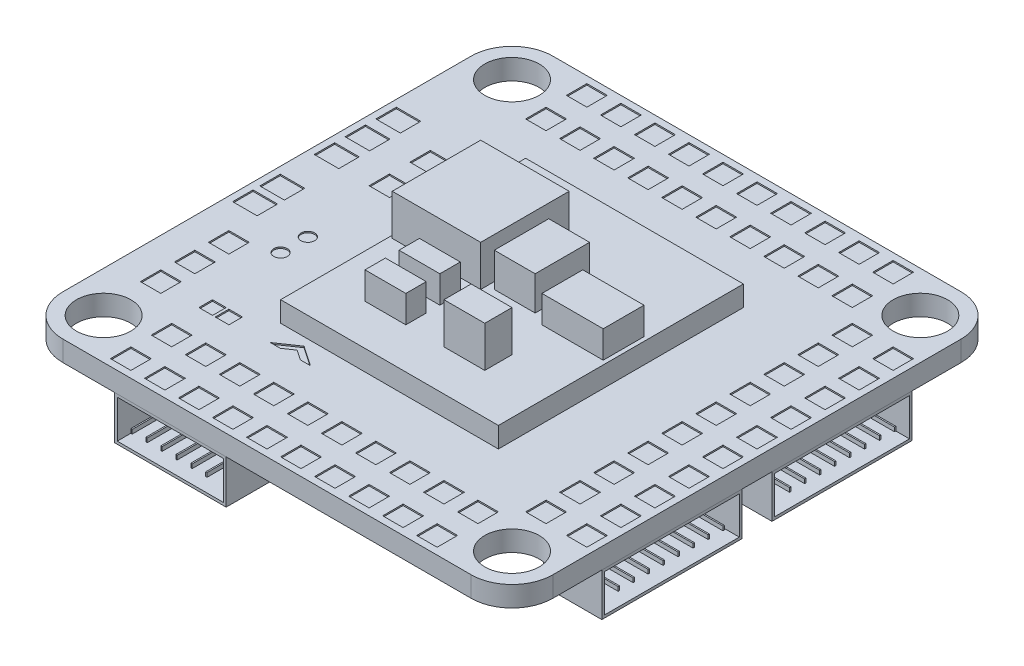
SolidWorks part; units mm, degrees
ref_plane "Front Plane" through (0, 0, 0) normal (0, 0, 1) x (1, 0, 0)
ref_plane "Top Plane" through (0, 0, 0) normal (0, 1, 0) x (1, 0, 0)
ref_plane "Right Plane" through (0, 0, 0) normal (1, 0, 0) x (0, 0, -1)
sketch "Sketch1" plane through (0, 0, 0) normal (0, 1, 0) x (1, 0, 0)
  line L1 (-15, 18) -> (15, 18)
  line L2 (-18, 15) -> (-18, -15)
  line L3 (-15, -18) -> (15, -18)
  line L4 (18, 15) -> (18, -15)
  line L5 (-18, 18) -> (18, -18) construction
  line L6 (-18, -18) -> (18, 18) construction
  circle A0 centre (-15, 15) radius 2
  circle A1 centre (15, 15) radius 2
  circle A2 centre (15, -15) radius 2
  circle A3 centre (-15, -15) radius 2
  arc A4 (-18, -15) -> (-15, -18) centre (-15, -15) ccw
  arc A5 (15, -18) -> (18, -15) centre (15, -15) ccw
  arc A6 (15, 18) -> (18, 15) centre (15, 15) cw
  arc A7 (-18, 15) -> (-15, 18) centre (-15, 15) cw
  point P0 (0, 0)
  dimension "D3" = 4
  dimension "D4" = 3
  dimension "D5" = 3
  dimension "D8" = 30
  dimension "D9" = 30
  dimension "D10" = 3
  dimension "D1" = 36
  dimension "D2" = 36
  dimension "D6" = 2
  dimension "D7" = 2
extrude "Boss-Extrude1" add sketch "Sketch1" along normal blind 1.5
sketch "Sketch2" plane through (0, 1.5, 0) normal (0, 1, 0) x (1, 0, 0)
  line L1 (-8, 9) -> (8, 9)
  line L2 (-8, 9) -> (-8, -9)
  line L3 (-8, -9) -> (8, -9)
  line L4 (8, 9) -> (8, -9)
  line L5 (-8, 9) -> (8, -9) construction
  line L6 (-8, -9) -> (8, 9) construction
  point P0 (0, 0)
  dimension "D1" = 16
  dimension "D2" = 18
extrude "Boss-Extrude2" add sketch "Sketch2" along normal blind 1.5
sketch "Sketch3" plane through (0, 3, 0) normal (0, 1, 0) x (1, 0, 0)
  line L0 (8, 9) -> (-8, 9) construction
  line L1 (-7.8, 5.5) -> (-1.3, 5.5)
  line L2 (-7.8, 5.5) -> (-7.8, -1)
  line L3 (-7.8, -1) -> (-1.3, -1)
  line L4 (-1.3, 5.5) -> (-1.3, -1)
  line L5 (-7.8, 5.5) -> (-1.3, -1) construction
  line L6 (-7.8, -1) -> (-1.3, 5.5) construction
  line L7 (8, -9) -> (8, 9) construction
  point P0 (-4.55, 2.25)
  dimension "D1" = 6.5
  dimension "D2" = 6.5
  dimension "D3" = 3.5
  dimension "D4" = 9.3
extrude "Boss-Extrude3" add sketch "Sketch3" along normal blind 3
sketch "Sketch4" plane through (0, 3, 0) normal (0, 1, 0) x (1, 0, 0)
  line L0 (-7.8, -1) -> (-1.3, -1) construction
  line L1 (-4.8, -2) -> (-1.8, -2)
  line L2 (-4.8, -2) -> (-4.8, -3.5)
  line L3 (-4.8, -3.5) -> (-1.8, -3.5)
  line L4 (-1.8, -2) -> (-1.8, -3.5)
  line L5 (-4.8, -2) -> (-1.8, -3.5) construction
  line L6 (-4.8, -3.5) -> (-1.8, -2) construction
  line L7 (-1.3, -1) -> (-1.3, 5.5) construction
  line L8 (-4.8, -4.5) -> (-4.8, -6)
  line L9 (-4.8, -4.5) -> (-1.8, -4.5)
  line L10 (-1.8, -4.5) -> (-1.8, -6)
  line L11 (-4.8, -6) -> (-1.8, -6)
  point P0 (-3.3, -2.75)
  dimension "D1" = 1.5
  dimension "D2" = 3
  dimension "D3" = 1
  dimension "D4" = 0.5
  dimension "D5" = 2
extrude "Boss-Extrude4" add sketch "Sketch4" along normal blind 2
sketch "Sketch5" plane through (0, 3, 0) normal (0, 1, 0) x (1, 0, 0)
  line L0 (8, -9) -> (8, 9) construction
  line L1 (1, -4) -> (4, -4)
  line L2 (1, -4) -> (1, -6)
  line L3 (1, -6) -> (4, -6)
  line L4 (4, -4) -> (4, -6)
  line L5 (1, -4) -> (4, -6) construction
  line L6 (1, -6) -> (4, -4) construction
  line L7 (-8, -9) -> (8, -9) construction
  point P0 (2.5, -5)
  dimension "D1" = 2
  dimension "D2" = 3
  dimension "D3" = 4
  dimension "D4" = 3
extrude "Boss-Extrude5" add sketch "Sketch5" along normal blind 3
sketch "Sketch6" plane through (0, 3, 0) normal (0, 1, 0) x (1, 0, 0)
  line L0 (-1.3, -1) -> (-1.3, 5.5) construction
  line L1 (-0.8, 3.5) -> (2.2, 3.5)
  line L2 (-0.8, 3.5) -> (-0.8, -0.5)
  line L3 (-0.8, -0.5) -> (2.2, -0.5)
  line L4 (2.2, 3.5) -> (2.2, -0.5)
  line L5 (-0.8, 3.5) -> (2.2, -0.5) construction
  line L6 (-0.8, -0.5) -> (2.2, 3.5) construction
  line L8 (-7.8, -1) -> (-1.3, -1) construction
  point P0 (0.7, 1.5)
  dimension "D1" = 4
  dimension "D2" = 3
  dimension "D3" = 0.5
  dimension "D4" = 0.5
extrude "Boss-Extrude6" add sketch "Sketch6" along normal blind 2.5
sketch "Sketch7" plane through (0, 3, 0) normal (0, 1, 0) x (1, 0, 0)
  line L0 (8, -9) -> (8, 9) construction
  line L1 (3.2, 2) -> (7.7, 2)
  line L2 (3.2, 2) -> (3.2, -1)
  line L3 (3.2, -1) -> (7.7, -1)
  line L4 (7.7, 2) -> (7.7, -1)
  line L5 (3.2, 2) -> (7.7, -1) construction
  line L6 (3.2, -1) -> (7.7, 2) construction
  line L7 (8, 9) -> (-8, 9) construction
  point P0 (5.45, 0.5)
  dimension "D1" = 4.5
  dimension "D2" = 3
  dimension "D3" = 0.3
  dimension "D4" = 7
extrude "Boss-Extrude7" add sketch "Sketch7" along normal blind 2
sketch "Sketch8" plane through (0, 1.5, 0) normal (0, 1, 0) x (1, 0, 0)
  line L0 (-5.6809, -9.5944) -> (-7.1537, -10.6043)
  line L1 (-7.1537, -10.6043) -> (-6.4173, -10.6043)
  line L2 (-6.4173, -10.6043) -> (-5.6809, -10.0993)
  line L3 (-5.6809, -9.5944) -> (-5.6809, -10.6043) construction
  line L4 (-4.9445, -10.6043) -> (-5.6809, -10.0993)
  line L5 (-4.2081, -10.6043) -> (-4.9445, -10.6043)
  line L6 (-5.6809, -9.5944) -> (-4.2081, -10.6043)
extrude "Cut-Extrude1" cut sketch "Sketch8" against normal blind 0.1
sketch "Sketch9" plane through (0, 1.5, 0) normal (0, 1, 0) x (1, 0, 0)
  line L0 (-18, 15) -> (-18, -15) construction
  line L1 (-12, -13) -> (-10.5, -13)
  line L2 (-12, -13) -> (-12, -14.5)
  line L3 (-12, -14.5) -> (-10.5, -14.5)
  line L4 (-10.5, -13) -> (-10.5, -14.5)
  line L5 (-12, -13) -> (-10.5, -14.5) construction
  line L6 (-12, -14.5) -> (-10.5, -13) construction
  line L7 (-15, -18) -> (15, -18) construction
  line L8 (-9.5, -13) -> (-9.5, -14.5)
  line L9 (-9.5, -13) -> (-8, -13)
  line L10 (-8, -13) -> (-8, -14.5)
  line L11 (-9.5, -14.5) -> (-8, -14.5)
  line L12 (-7, -13) -> (-7, -14.5)
  line L13 (-7, -13) -> (-5.5, -13)
  line L14 (-5.5, -13) -> (-5.5, -14.5)
  line L15 (-7, -14.5) -> (-5.5, -14.5)
  line L16 (-4.5, -13) -> (-4.5, -14.5)
  line L17 (-4.5, -13) -> (-3, -13)
  line L18 (-3, -13) -> (-3, -14.5)
  line L19 (-4.5, -14.5) -> (-3, -14.5)
  line L20 (-2, -13) -> (-2, -14.5)
  line L21 (-2, -13) -> (-0.5, -13)
  line L22 (-0.5, -13) -> (-0.5, -14.5)
  line L23 (-2, -14.5) -> (-0.5, -14.5)
  line L24 (0.5, -13) -> (0.5, -14.5)
  line L25 (0.5, -13) -> (2, -13)
  line L26 (2, -13) -> (2, -14.5)
  line L27 (0.5, -14.5) -> (2, -14.5)
  line L28 (3, -13) -> (3, -14.5)
  line L29 (3, -13) -> (4.5, -13)
  line L30 (4.5, -13) -> (4.5, -14.5)
  line L31 (3, -14.5) -> (4.5, -14.5)
  line L32 (5.5, -13) -> (5.5, -14.5)
  line L33 (5.5, -13) -> (7, -13)
  line L34 (7, -13) -> (7, -14.5)
  line L35 (5.5, -14.5) -> (7, -14.5)
  line L36 (8, -13) -> (8, -14.5)
  line L37 (8, -13) -> (9.5, -13)
  line L38 (9.5, -13) -> (9.5, -14.5)
  line L39 (8, -14.5) -> (9.5, -14.5)
  line L40 (10.5, -13) -> (10.5, -14.5)
  line L41 (10.5, -13) -> (12, -13)
  line L42 (12, -13) -> (12, -14.5)
  line L43 (10.5, -14.5) -> (12, -14.5)
  line L44 (-9.5, -16) -> (-9.5, -17.5)
  line L45 (-9.5, -16) -> (-8, -16)
  line L46 (-8, -16) -> (-8, -17.5)
  line L47 (-9.5, -17.5) -> (-8, -17.5)
  line L48 (-7, -16) -> (-7, -17.5)
  line L49 (-7, -16) -> (-5.5, -16)
  line L50 (-5.5, -16) -> (-5.5, -17.5)
  line L51 (-7, -17.5) -> (-5.5, -17.5)
  line L52 (-4.5, -16) -> (-4.5, -17.5)
  line L53 (-4.5, -16) -> (-3, -16)
  line L54 (-3, -16) -> (-3, -17.5)
  line L55 (-4.5, -17.5) -> (-3, -17.5)
  line L56 (-2, -16) -> (-2, -17.5)
  line L57 (-2, -16) -> (-0.5, -16)
  line L58 (-0.5, -16) -> (-0.5, -17.5)
  line L59 (-2, -17.5) -> (-0.5, -17.5)
  line L60 (0.5, -16) -> (0.5, -17.5)
  line L61 (0.5, -16) -> (2, -16)
  line L62 (2, -16) -> (2, -17.5)
  line L63 (0.5, -17.5) -> (2, -17.5)
  line L64 (3, -16) -> (3, -17.5)
  line L65 (3, -16) -> (4.5, -16)
  line L66 (4.5, -16) -> (4.5, -17.5)
  line L67 (3, -17.5) -> (4.5, -17.5)
  line L68 (5.5, -16) -> (5.5, -17.5)
  line L69 (5.5, -16) -> (7, -16)
  line L70 (7, -16) -> (7, -17.5)
  line L71 (5.5, -17.5) -> (7, -17.5)
  line L72 (8, -16) -> (8, -17.5)
  line L73 (8, -16) -> (9.5, -16)
  line L74 (9.5, -16) -> (9.5, -17.5)
  line L75 (8, -17.5) -> (9.5, -17.5)
  line L76 (10.5, -16) -> (10.5, -17.5)
  line L77 (10.5, -16) -> (12, -16)
  line L78 (12, -16) -> (12, -17.5)
  line L79 (10.5, -17.5) -> (12, -17.5)
  line L80 (-12, -16) -> (-12, -17.5)
  line L81 (-12, -16) -> (-10.5, -16)
  line L82 (-10.5, -16) -> (-10.5, -17.5)
  line L83 (-12, -17.5) -> (-10.5, -17.5)
  line L84 (-18, 0) -> (18, 0) construction
  line L85 (18, -15) -> (18, 15) construction
  line L86 (-15, 15) -> (15, -15) construction
  line L87 (14.5, 12) -> (13, 10.5) construction
  line L88 (13, 12) -> (14.5, 10.5) construction
  line L89 (17.5, 12) -> (17.5, 10.5)
  line L90 (16, 10.5) -> (17.5, 10.5)
  line L91 (16, 12) -> (16, 10.5)
  line L92 (16, 12) -> (17.5, 12)
  line L93 (17.5, -10.5) -> (17.5, -12)
  line L94 (16, -12) -> (17.5, -12)
  line L95 (16, -10.5) -> (16, -12)
  line L96 (16, -10.5) -> (17.5, -10.5)
  line L97 (17.5, -8) -> (17.5, -9.5)
  line L98 (16, -9.5) -> (17.5, -9.5)
  line L99 (16, -8) -> (16, -9.5)
  line L100 (16, -8) -> (17.5, -8)
  line L101 (17.5, -5.5) -> (17.5, -7)
  line L102 (16, -7) -> (17.5, -7)
  line L103 (16, -5.5) -> (16, -7)
  line L104 (16, -5.5) -> (17.5, -5.5)
  line L105 (17.5, -3) -> (17.5, -4.5)
  line L106 (16, -4.5) -> (17.5, -4.5)
  line L107 (16, -3) -> (16, -4.5)
  line L108 (16, -3) -> (17.5, -3)
  line L109 (17.5, -0.5) -> (17.5, -2)
  line L110 (16, -2) -> (17.5, -2)
  line L111 (16, -0.5) -> (16, -2)
  line L112 (16, -0.5) -> (17.5, -0.5)
  line L113 (17.5, 2) -> (17.5, 0.5)
  line L114 (16, 0.5) -> (17.5, 0.5)
  line L115 (16, 2) -> (16, 0.5)
  line L116 (16, 2) -> (17.5, 2)
  line L117 (17.5, 4.5) -> (17.5, 3)
  line L118 (16, 3) -> (17.5, 3)
  line L119 (16, 4.5) -> (16, 3)
  line L120 (16, 4.5) -> (17.5, 4.5)
  line L121 (17.5, 7) -> (17.5, 5.5)
  line L122 (16, 5.5) -> (17.5, 5.5)
  line L123 (16, 7) -> (16, 5.5)
  line L124 (16, 7) -> (17.5, 7)
  line L125 (17.5, 9.5) -> (17.5, 8)
  line L126 (16, 8) -> (17.5, 8)
  line L127 (16, 9.5) -> (16, 8)
  line L128 (16, 9.5) -> (17.5, 9.5)
  line L129 (14.5, -10.5) -> (14.5, -12)
  line L130 (13, -12) -> (14.5, -12)
  line L131 (13, -10.5) -> (13, -12)
  line L132 (13, -10.5) -> (14.5, -10.5)
  line L133 (14.5, -8) -> (14.5, -9.5)
  line L134 (13, -9.5) -> (14.5, -9.5)
  line L135 (13, -8) -> (13, -9.5)
  line L136 (13, -8) -> (14.5, -8)
  line L137 (14.5, -5.5) -> (14.5, -7)
  line L138 (13, -7) -> (14.5, -7)
  line L139 (13, -5.5) -> (13, -7)
  line L140 (13, -5.5) -> (14.5, -5.5)
  line L141 (14.5, -3) -> (14.5, -4.5)
  line L142 (13, -4.5) -> (14.5, -4.5)
  line L143 (13, -3) -> (13, -4.5)
  line L144 (13, -3) -> (14.5, -3)
  line L145 (14.5, -0.5) -> (14.5, -2)
  line L146 (13, -2) -> (14.5, -2)
  line L147 (13, -0.5) -> (13, -2)
  line L148 (13, -0.5) -> (14.5, -0.5)
  line L149 (14.5, 2) -> (14.5, 0.5)
  line L150 (13, 0.5) -> (14.5, 0.5)
  line L151 (13, 2) -> (13, 0.5)
  line L152 (13, 2) -> (14.5, 2)
  line L153 (14.5, 4.5) -> (14.5, 3)
  line L154 (13, 3) -> (14.5, 3)
  line L155 (13, 4.5) -> (13, 3)
  line L156 (13, 4.5) -> (14.5, 4.5)
  line L157 (14.5, 7) -> (14.5, 5.5)
  line L158 (13, 5.5) -> (14.5, 5.5)
  line L159 (13, 7) -> (13, 5.5)
  line L160 (13, 7) -> (14.5, 7)
  line L161 (14.5, 9.5) -> (14.5, 8)
  line L162 (13, 8) -> (14.5, 8)
  line L163 (13, 9.5) -> (13, 8)
  line L164 (13, 9.5) -> (14.5, 9.5)
  line L165 (13, 10.5) -> (14.5, 10.5)
  line L166 (14.5, 12) -> (14.5, 10.5)
  line L167 (13, 12) -> (14.5, 12)
  line L168 (13, 12) -> (13, 10.5)
  line L169 (-12, 14.5) -> (-10.5, 13) construction
  line L170 (-12, 13) -> (-10.5, 14.5) construction
  line L171 (-12, 17.5) -> (-10.5, 17.5)
  line L172 (-10.5, 16) -> (-10.5, 17.5)
  line L173 (-12, 16) -> (-10.5, 16)
  line L174 (-12, 16) -> (-12, 17.5)
  line L175 (10.5, 17.5) -> (12, 17.5)
  line L176 (12, 16) -> (12, 17.5)
  line L177 (10.5, 16) -> (12, 16)
  line L178 (10.5, 16) -> (10.5, 17.5)
  line L179 (8, 17.5) -> (9.5, 17.5)
  line L180 (9.5, 16) -> (9.5, 17.5)
  line L181 (8, 16) -> (9.5, 16)
  line L182 (8, 16) -> (8, 17.5)
  line L183 (5.5, 17.5) -> (7, 17.5)
  line L184 (7, 16) -> (7, 17.5)
  line L185 (5.5, 16) -> (7, 16)
  line L186 (5.5, 16) -> (5.5, 17.5)
  line L187 (3, 17.5) -> (4.5, 17.5)
  line L188 (4.5, 16) -> (4.5, 17.5)
  line L189 (3, 16) -> (4.5, 16)
  line L190 (3, 16) -> (3, 17.5)
  line L191 (0.5, 17.5) -> (2, 17.5)
  line L192 (2, 16) -> (2, 17.5)
  line L193 (0.5, 16) -> (2, 16)
  line L194 (0.5, 16) -> (0.5, 17.5)
  line L195 (-2, 17.5) -> (-0.5, 17.5)
  line L196 (-0.5, 16) -> (-0.5, 17.5)
  line L197 (-2, 16) -> (-0.5, 16)
  line L198 (-2, 16) -> (-2, 17.5)
  line L199 (-4.5, 17.5) -> (-3, 17.5)
  line L200 (-3, 16) -> (-3, 17.5)
  line L201 (-4.5, 16) -> (-3, 16)
  line L202 (-4.5, 16) -> (-4.5, 17.5)
  line L203 (-7, 17.5) -> (-5.5, 17.5)
  line L204 (-5.5, 16) -> (-5.5, 17.5)
  line L205 (-7, 16) -> (-5.5, 16)
  line L206 (-7, 16) -> (-7, 17.5)
  line L207 (-9.5, 17.5) -> (-8, 17.5)
  line L208 (-8, 16) -> (-8, 17.5)
  line L209 (-9.5, 16) -> (-8, 16)
  line L210 (-9.5, 16) -> (-9.5, 17.5)
  line L211 (10.5, 14.5) -> (12, 14.5)
  line L212 (12, 13) -> (12, 14.5)
  line L213 (10.5, 13) -> (12, 13)
  line L214 (10.5, 13) -> (10.5, 14.5)
  line L215 (8, 14.5) -> (9.5, 14.5)
  line L216 (9.5, 13) -> (9.5, 14.5)
  line L217 (8, 13) -> (9.5, 13)
  line L218 (8, 13) -> (8, 14.5)
  line L219 (5.5, 14.5) -> (7, 14.5)
  line L220 (7, 13) -> (7, 14.5)
  line L221 (5.5, 13) -> (7, 13)
  line L222 (5.5, 13) -> (5.5, 14.5)
  line L223 (3, 14.5) -> (4.5, 14.5)
  line L224 (4.5, 13) -> (4.5, 14.5)
  line L225 (3, 13) -> (4.5, 13)
  line L226 (3, 13) -> (3, 14.5)
  line L227 (0.5, 14.5) -> (2, 14.5)
  line L228 (2, 13) -> (2, 14.5)
  line L229 (0.5, 13) -> (2, 13)
  line L230 (0.5, 13) -> (0.5, 14.5)
  line L231 (-2, 14.5) -> (-0.5, 14.5)
  line L232 (-0.5, 13) -> (-0.5, 14.5)
  line L233 (-2, 13) -> (-0.5, 13)
  line L234 (-2, 13) -> (-2, 14.5)
  line L235 (-4.5, 14.5) -> (-3, 14.5)
  line L236 (-3, 13) -> (-3, 14.5)
  line L237 (-4.5, 13) -> (-3, 13)
  line L238 (-4.5, 13) -> (-4.5, 14.5)
  line L239 (-7, 14.5) -> (-5.5, 14.5)
  line L240 (-5.5, 13) -> (-5.5, 14.5)
  line L241 (-7, 13) -> (-5.5, 13)
  line L242 (-7, 13) -> (-7, 14.5)
  line L243 (-9.5, 14.5) -> (-8, 14.5)
  line L244 (-8, 13) -> (-8, 14.5)
  line L245 (-9.5, 13) -> (-8, 13)
  line L246 (-9.5, 13) -> (-9.5, 14.5)
  line L247 (-10.5, 13) -> (-10.5, 14.5)
  line L248 (-12, 14.5) -> (-10.5, 14.5)
  line L249 (-12, 13) -> (-12, 14.5)
  line L250 (-12, 13) -> (-10.5, 13)
  line L251 (-10.8, -10) -> (-10.8, -11)
  line L252 (-12, -10) -> (-11, -10)
  line L253 (-12, -10) -> (-12, -11)
  line L254 (-12, -11) -> (-11, -11)
  line L255 (-11, -10) -> (-11, -11)
  line L256 (-12, -10) -> (-11, -11) construction
  line L257 (-12, -11) -> (-11, -10) construction
  line L258 (-10.8, -10) -> (-9.8, -10)
  line L259 (-9.8, -10) -> (-9.8, -11)
  line L260 (-10.8, -11) -> (-9.8, -11)
  line L261 (-10.5, -16) -> (-12, -17.5) construction
  line L262 (-8, -13) -> (-9.5, -14.5) construction
  line L263 (-8, -16) -> (-9.5, -17.5) construction
  line L264 (-12, -16) -> (-10.5, -17.5) construction
  line L265 (-9.5, -16) -> (-8, -17.5) construction
  line L266 (-9.5, -13) -> (-8, -14.5) construction
  line L267 (-10.8, -10) -> (-9.8, -11) construction
  line L268 (-9.8, -10) -> (-10.8, -11) construction
  line L269 (-7, -13) -> (-5.5, -14.5) construction
  line L270 (-5.5, -16) -> (-7, -17.5) construction
  line L271 (-4.5, -14.5) -> (-3, -13) construction
  line L272 (15, 18) -> (-15, 18) construction
  line L273 (-15.7, 9) -> (-17.5, 9)
  line L274 (-15.7, 9) -> (-15.7, 7.5)
  line L275 (-15.7, 7.5) -> (-17.5, 7.5)
  line L276 (-17.5, 9) -> (-17.5, 7.5)
  line L277 (-15.7, 9) -> (-17.5, 7.5) construction
  line L278 (-15.7, 7.5) -> (-17.5, 9) construction
  line L279 (-15.7, 6.7373) -> (-15.7, 5.2373)
  line L280 (-15.7, 6.7373) -> (-17.5, 6.7373)
  line L281 (-17.5, 6.7373) -> (-17.5, 5.2373)
  line L282 (-15.7, 5.2373) -> (-17.5, 5.2373)
  line L283 (-15.7, 4.4745) -> (-15.7, 2.9745)
  line L284 (-15.7, 4.4745) -> (-17.5, 4.4745)
  line L285 (-17.5, 4.4745) -> (-17.5, 2.9745)
  line L286 (-15.7, 2.9745) -> (-17.5, 2.9745)
  line L287 (-15.7, -1.5255) -> (-15.7, -3.0255)
  line L288 (-15.7, 0.4745) -> (-17.5, 0.4745)
  line L289 (-15.7, 0.4745) -> (-15.7, -1.0255)
  line L290 (-15.7, -1.0255) -> (-17.5, -1.0255)
  line L291 (-17.5, 0.4745) -> (-17.5, -1.0255)
  line L292 (-15.7, 0.4745) -> (-17.5, -1.0255) construction
  line L293 (-15.7, -1.0255) -> (-17.5, 0.4745) construction
  line L294 (-15.7, -1.5255) -> (-17.5, -1.5255)
  line L295 (-17.5, -1.5255) -> (-17.5, -3.0255)
  line L296 (-15.7, -3.0255) -> (-17.5, -3.0255)
  line L297 (-12, 4.5) -> (-12, 3)
  line L298 (-12, 7.5) -> (-13.5, 7.5)
  line L299 (-12, 7.5) -> (-12, 6)
  line L300 (-12, 6) -> (-13.5, 6)
  line L301 (-13.5, 7.5) -> (-13.5, 6)
  line L302 (-12, 7.5) -> (-13.5, 6) construction
  line L303 (-12, 6) -> (-13.5, 7.5) construction
  line L304 (-12, 4.5) -> (-13.5, 4.5)
  line L305 (-13.5, 4.5) -> (-13.5, 3)
  line L306 (-12, 3) -> (-13.5, 3)
  line L307 (-14.3, -7.5) -> (-14.3, -9)
  line L308 (-14.3, -10) -> (-15.8, -10)
  line L309 (-14.3, -10) -> (-14.3, -11.5)
  line L310 (-14.3, -11.5) -> (-15.8, -11.5)
  line L311 (-15.8, -10) -> (-15.8, -11.5)
  line L312 (-14.3, -10) -> (-15.8, -11.5) construction
  line L313 (-14.3, -11.5) -> (-15.8, -10) construction
  line L314 (-14.3, -7.5) -> (-15.8, -7.5)
  line L315 (-15.8, -7.5) -> (-15.8, -9)
  line L316 (-14.3, -9) -> (-15.8, -9)
  line L317 (-14.3, -5) -> (-14.3, -6.5)
  line L318 (-14.3, -5) -> (-15.8, -5)
  line L319 (-15.8, -5) -> (-15.8, -6.5)
  line L320 (-14.3, -6.5) -> (-15.8, -6.5)
  circle A0 centre (-12.5, -4.5) radius 0.5
  circle A1 centre (-12.5, -2.5) radius 0.5
  point P0 (-11.25, -13.75)
  point P173 (13.75, 11.25)
  point P254 (-11.25, 13.75)
  point P255 (-11.5, -10.5)
  point P260 (-16.6, 8.25)
  point P271 (-16.6, -0.2755)
  point P284 (-12.75, 6.75)
  point P293 (-15.05, -10.75)
  dimension "D32" = 1
  dimension "D33" = 5.5
  dimension "D34" = 13.5
  dimension "D1" = 1.5
  dimension "D2" = 1.5
  dimension "D3" = 6
  dimension "D4" = 3.5
  dimension "D7" = 1
  dimension "D8" = 1
  dimension "D9" = 0
  dimension "D10" = 2
  dimension "D12" = 9
  dimension "D13" = 1.5
  dimension "D14" = 1.8
  dimension "D16" = 1.5
  dimension "D17" = 1.8
  dimension "D18" = 2.5
  dimension "D19" = 0.5
  dimension "D20" = 0.5
  dimension "D22" = 1.5
  dimension "D23" = 1.5
  dimension "D24" = 4.5
  dimension "D25" = 10.5
  dimension "D27" = 1.5
  dimension "D28" = 1.5
  dimension "D29" = 6.5
  dimension "D30" = 2.2
  dimension "D5" = 10
  dimension "D6" = 2
  dimension "D11" = 2
  dimension "D15" = 3
  dimension "D21" = 2
  dimension "D26" = 2
  dimension "D31" = 3
  dimension "D35" = 2
extrude "Cut-Extrude2" cut sketch "Sketch9" against normal blind 0.1
sketch "Sketch12" plane through (-18, 0, 0) normal (-1, 0, 0) x (0, 0, 1)
  line L1 (-8.7, 0) -> (-3.1, 0)
  line L3 (-8.7, -3.2) -> (-3.1, -3.2)
  line L6 (-18, 1.5) -> (-18, 0) construction
  line L7 (-15, 0) -> (15, 0) construction
  arc A0 (-3.1, 0) -> (-3.1, -3.2) centre (-3.1, -1.6) cw
  arc A1 (-8.7, -3.2) -> (-8.7, 0) centre (-8.7, -1.6) cw
  dimension "D1" = 1.6
  dimension "D2" = 1.6
  dimension "D3" = 9.3
  dimension "D6" = 5.6
  dimension "D4" = 5.6
  dimension "D5" = 3.2
  dimension "D7" = 3.2
extrude "Boss-Extrude8" add sketch "Sketch12" along normal blind 1.5 and the other way blind 5.7
sketch "Sketch13" plane through (-19.5, 0, 0) normal (-1, 0, 0) x (0, 0, 1)
  line L0 (-3.1, 0) -> (-8.7, 0) construction
  line L1 (-8.7, 0) -> (-3.1, 0)
  line L2 (-3.1, -3.2) -> (-8.7, -3.2)
  line L3 (-3.1, -3.1) -> (-8.7, -3.1)
  line L4 (-8.7, -0.1) -> (-3.1, -0.1)
  line L5 (-8.7, -1.6) -> (-3.1, -1.6) construction
  line L6 (-8.7, -1.8) -> (-3.1, -1.8)
  line L7 (-8.7, -1.4) -> (-3.1, -1.4)
  arc A0 (-8.7, -3.2) -> (-8.7, 0) centre (-8.7, -1.6) cw
  arc A1 (-3.1, 0) -> (-3.1, -3.2) centre (-3.1, -1.6) cw
  arc A2 (-3.1, -3.2) -> (-3.1, 0) centre (-3.1, -1.6) ccw construction
  arc A3 (-8.7, -3.1) -> (-8.7, -0.1) centre (-8.7, -1.6) cw
  arc A4 (-3.1, -0.1) -> (-3.1, -3.1) centre (-3.1, -1.6) cw
  arc A5 (-3.1, -1.4) -> (-3.1, -1.8) centre (-3.1, -1.6) cw
  arc A6 (-8.7, -1.8) -> (-8.7, -1.4) centre (-8.7, -1.6) cw
  dimension "D1" = 0.1
  dimension "D2" = 0.2
  dimension "D3" = 0.2
extrude "Cut-Extrude3" cut sketch "Sketch13" against normal blind 6 contours A4 L4 A3 L3 L6 A6 L7 A5
sketch "Sketch15" plane through (0, 0, 0) normal (0, -1, 0) x (1, 0, 0)
  line L1 (-17.7, 5) -> (-15.2, 5)
  line L2 (-17.7, 5) -> (-17.7, 9.5)
  line L3 (-17.7, 9.5) -> (-15.2, 9.5)
  line L4 (-15.2, 5) -> (-15.2, 9.5)
  line L5 (-17.7, 5) -> (-15.2, 9.5) construction
  line L6 (-17.7, 9.5) -> (-15.2, 5) construction
  line L8 (-12.3, -1.5) -> (-19.5, -1.5) construction
  line L9 (-18, -3.1) -> (-18, 15) construction
  point P0 (-16.45, 7.25)
  dimension "D1" = 6.5
  dimension "D2" = 2.8
  dimension "D3" = 2.5
  dimension "D4" = 4.5
extrude "Boss-Extrude9" add sketch "Sketch15" along normal blind 2
sketch "Sketch16" plane through (-17.7, 0, 0) normal (-1, 0, 0) x (0, 0, 1)
  line L0 (5, 0) -> (9.5, -2) construction
  line L1 (9.5, 0) -> (5, -2) construction
  line L3 (6.25, -0.5) -> (8.25, -0.5)
  line L4 (6.25, -0.5) -> (6.25, -1.5)
  line L5 (6.25, -1.5) -> (8.25, -1.5)
  line L6 (8.25, -0.5) -> (8.25, -1.5)
  line L7 (6.25, -0.5) -> (8.25, -1.5) construction
  line L8 (6.25, -1.5) -> (8.25, -0.5) construction
  point P8 (7.25, -1)
  dimension "D1" = 2
  dimension "D2" = 1
extrude "Boss-Extrude10" add sketch "Sketch16" along normal blind 1
sketch "Sketch17" plane through (0, 0, 18) normal (0, 0, 1) x (1, 0, 0)
  line L0 (-15, 0) -> (15, 0) construction
  line L1 (-11.2, 0) -> (-3, 0)
  line L2 (-11.2, 0) -> (-11.2, -3.2)
  line L3 (-11.2, -3.2) -> (-3, -3.2)
  line L4 (-3, 0) -> (-3, -3.2)
  line L5 (-18, 1.5) -> (-18, 0) construction
  dimension "D1" = 15
  dimension "D2" = 8.2
  dimension "D3" = 3.2
extrude "Boss-Extrude11" add sketch "Sketch17" against normal blind 4.5 separate body
sketch "Sketch18" plane through (0, 0, 18) normal (0, 0, 1) x (1, 0, 0)
  line L0 (-11.2, 0) -> (-11.2, -3.2)
  line L1 (-11.2, -3.2) -> (-3, -3.2)
  line L2 (-3, -3.2) -> (-3, 0)
  line L3 (-3, 0) -> (-11.2, 0)
  line L4 (-3.2, -0.2) -> (-11, -0.2)
  line L5 (-11, -0.2) -> (-11, -3)
  line L6 (-11, -3) -> (-3.2, -3)
  line L7 (-3.2, -3) -> (-3.2, -0.2)
  line L8 (-8.9, -1.7) -> (-8.9, -2)
  line L9 (-10, -1.7) -> (-9.9, -1.7)
  line L10 (-10, -1.7) -> (-10, -2)
  line L11 (-10, -2) -> (-9.9, -2)
  line L12 (-9.9, -1.7) -> (-9.9, -2)
  line L13 (-10, -1.7) -> (-9.9, -2) construction
  line L14 (-10, -2) -> (-9.9, -1.7) construction
  line L15 (-8.9, -1.7) -> (-8.8, -1.7)
  line L16 (-8.8, -1.7) -> (-8.8, -2)
  line L17 (-8.9, -2) -> (-8.8, -2)
  line L18 (-7.8, -1.7) -> (-7.8, -2)
  line L19 (-7.8, -1.7) -> (-7.7, -1.7)
  line L20 (-7.7, -1.7) -> (-7.7, -2)
  line L21 (-7.8, -2) -> (-7.7, -2)
  line L22 (-6.7, -1.7) -> (-6.7, -2)
  line L23 (-6.7, -1.7) -> (-6.6, -1.7)
  line L24 (-6.6, -1.7) -> (-6.6, -2)
  line L25 (-6.7, -2) -> (-6.6, -2)
  line L26 (-5.6, -1.7) -> (-5.6, -2)
  line L27 (-5.6, -1.7) -> (-5.5, -1.7)
  line L28 (-5.5, -1.7) -> (-5.5, -2)
  line L29 (-5.6, -2) -> (-5.5, -2)
  line L30 (-4.5, -1.7) -> (-4.5, -2)
  line L31 (-4.5, -1.7) -> (-4.4, -1.7)
  line L32 (-4.4, -1.7) -> (-4.4, -2)
  line L33 (-4.5, -2) -> (-4.4, -2)
  point P12 (-9.95, -1.85)
  point P17 (-9.95, -2)
  dimension "D2" = 0.1
  dimension "D3" = 0.3
  dimension "D4" = 1
  dimension "D5" = 1
  dimension "D1" = 0.2
  dimension "D6" = 6
extrude "Cut-Extrude4" cut sketch "Sketch18" against normal blind 4 contours L6 L7 L4 L5 L33 L30 L31 L32 L29 L26 L27 L28 L25 L22 L23 L24 L21 L18 L19 L20 L17 L8 L15 L16 L9 L12 L11 L10
sketch "Sketch19" plane through (18, 0, 0) normal (1, 0, 0) x (0, 0, -1)
  line L0 (-15, 0) -> (15, 0) construction
  line L1 (-11.4, 0) -> (-1.1, 0)
  line L2 (-11.4, 0) -> (-11.4, -3.1558)
  line L3 (-11.4, -3.1558) -> (-1.1, -3.1558)
  line L4 (-1.1, 0) -> (-1.1, -3.1558)
  line L5 (-18, 1.5) -> (-18, 0) construction
  line L6 (0, 0) -> (0, -3.1558) construction
  line L7 (1.1, 0) -> (1.1, -3.1558)
  line L8 (11.4, -3.1558) -> (1.1, -3.1558)
  line L9 (11.4, 0) -> (11.4, -3.1558)
  line L10 (11.4, 0) -> (1.1, 0)
  dimension "D1" = 10.3
  dimension "D2" = 6.6
extrude "Boss-Extrude12" add sketch "Sketch19" against normal blind 4.3 separate body
sketch "Sketch20" plane through (18, 0, 0) normal (1, 0, 0) x (0, 0, -1)
  line L0 (-11.2, -0.2) -> (-11.2, -2.9558)
  line L1 (-11.4, 0) -> (-1.1, 0)
  line L2 (-11.4, 0) -> (-11.4, -3.1558)
  line L3 (-11.4, -3.1558) -> (-1.1, -3.1558)
  line L4 (-1.1, 0) -> (-1.1, -3.1558)
  line L5 (1.1, 0) -> (11.4, 0)
  line L6 (1.1, 0) -> (1.1, -3.1558)
  line L7 (1.1, -3.1558) -> (11.4, -3.1558)
  line L8 (11.4, 0) -> (11.4, -3.1558)
  line L9 (-11.2, -2.9558) -> (-1.3, -2.9558)
  line L10 (-1.3, -0.2) -> (-1.3, -2.9558)
  line L11 (-11.2, -0.2) -> (-1.3, -0.2)
  line L12 (1.3, -0.2) -> (1.3, -2.9558)
  line L13 (1.3, -2.9558) -> (11.2, -2.9558)
  line L14 (11.2, -0.2) -> (11.2, -2.9558)
  line L15 (1.3, -0.2) -> (11.2, -0.2)
  line L16 (0, 0) -> (0, -3.1558) construction
  line L17 (-10.2, -1.6558) -> (-10.1, -1.6558)
  line L18 (-10.2, -1.6558) -> (-10.2, -1.9558)
  line L19 (-10.2, -1.9558) -> (-10.1, -1.9558)
  line L20 (-10.1, -1.6558) -> (-10.1, -1.9558)
  line L21 (-10.2, -1.6558) -> (-10.1, -1.9558) construction
  line L22 (-10.2, -1.9558) -> (-10.1, -1.6558) construction
  line L23 (-9.1, -1.6558) -> (-9.1, -1.9558)
  line L24 (-9.1, -1.6558) -> (-9, -1.6558)
  line L25 (-9, -1.6558) -> (-9, -1.9558)
  line L26 (-9.1, -1.9558) -> (-9, -1.9558)
  line L27 (-8, -1.6558) -> (-8, -1.9558)
  line L28 (-8, -1.6558) -> (-7.9, -1.6558)
  line L29 (-7.9, -1.6558) -> (-7.9, -1.9558)
  line L30 (-8, -1.9558) -> (-7.9, -1.9558)
  line L31 (-6.9, -1.6558) -> (-6.9, -1.9558)
  line L32 (-6.9, -1.6558) -> (-6.8, -1.6558)
  line L33 (-6.8, -1.6558) -> (-6.8, -1.9558)
  line L34 (-6.9, -1.9558) -> (-6.8, -1.9558)
  line L35 (-5.8, -1.6558) -> (-5.8, -1.9558)
  line L36 (-5.8, -1.6558) -> (-5.7, -1.6558)
  line L37 (-5.7, -1.6558) -> (-5.7, -1.9558)
  line L38 (-5.8, -1.9558) -> (-5.7, -1.9558)
  line L39 (-4.7, -1.6558) -> (-4.7, -1.9558)
  line L40 (-4.7, -1.6558) -> (-4.6, -1.6558)
  line L41 (-4.6, -1.6558) -> (-4.6, -1.9558)
  line L42 (-4.7, -1.9558) -> (-4.6, -1.9558)
  line L43 (-3.6, -1.6558) -> (-3.6, -1.9558)
  line L44 (-3.6, -1.6558) -> (-3.5, -1.6558)
  line L45 (-3.5, -1.6558) -> (-3.5, -1.9558)
  line L46 (-3.6, -1.9558) -> (-3.5, -1.9558)
  line L47 (-2.5, -1.6558) -> (-2.5, -1.9558)
  line L48 (-2.5, -1.6558) -> (-2.4, -1.6558)
  line L49 (-2.4, -1.6558) -> (-2.4, -1.9558)
  line L50 (-2.5, -1.9558) -> (-2.4, -1.9558)
  line L51 (10.2, -1.9558) -> (10.1, -1.6558) construction
  line L52 (10.2, -1.6558) -> (10.1, -1.9558) construction
  line L53 (2.5, -1.9558) -> (2.4, -1.9558)
  line L54 (2.4, -1.6558) -> (2.4, -1.9558)
  line L55 (2.5, -1.6558) -> (2.4, -1.6558)
  line L56 (2.5, -1.6558) -> (2.5, -1.9558)
  line L57 (3.6, -1.9558) -> (3.5, -1.9558)
  line L58 (3.5, -1.6558) -> (3.5, -1.9558)
  line L59 (3.6, -1.6558) -> (3.5, -1.6558)
  line L60 (3.6, -1.6558) -> (3.6, -1.9558)
  line L61 (4.7, -1.9558) -> (4.6, -1.9558)
  line L62 (4.6, -1.6558) -> (4.6, -1.9558)
  line L63 (4.7, -1.6558) -> (4.6, -1.6558)
  line L64 (4.7, -1.6558) -> (4.7, -1.9558)
  line L65 (5.8, -1.9558) -> (5.7, -1.9558)
  line L66 (5.7, -1.6558) -> (5.7, -1.9558)
  line L67 (5.8, -1.6558) -> (5.7, -1.6558)
  line L68 (5.8, -1.6558) -> (5.8, -1.9558)
  line L69 (6.9, -1.9558) -> (6.8, -1.9558)
  line L70 (6.8, -1.6558) -> (6.8, -1.9558)
  line L71 (6.9, -1.6558) -> (6.8, -1.6558)
  line L72 (6.9, -1.6558) -> (6.9, -1.9558)
  line L73 (8, -1.9558) -> (7.9, -1.9558)
  line L74 (7.9, -1.6558) -> (7.9, -1.9558)
  line L75 (8, -1.6558) -> (7.9, -1.6558)
  line L76 (8, -1.6558) -> (8, -1.9558)
  line L77 (9.1, -1.9558) -> (9, -1.9558)
  line L78 (9, -1.6558) -> (9, -1.9558)
  line L79 (9.1, -1.6558) -> (9, -1.6558)
  line L80 (9.1, -1.6558) -> (9.1, -1.9558)
  line L81 (10.1, -1.6558) -> (10.1, -1.9558)
  line L82 (10.2, -1.9558) -> (10.1, -1.9558)
  line L83 (10.2, -1.6558) -> (10.2, -1.9558)
  line L84 (10.2, -1.6558) -> (10.1, -1.6558)
  point P20 (-10.15, -1.8058)
  point P88 (10.15, -1.8058)
  dimension "D3" = 0.1
  dimension "D4" = 0.3
  dimension "D5" = 1
  dimension "D6" = 1
  dimension "D1" = 0.2
  dimension "D2" = 0.2
  dimension "D7" = 8
extrude "Cut-Extrude5" cut sketch "Sketch20" against normal blind 3.5 contours L11 L0 L9 L10 L50 L47 L48 L49 L46 L43 L44 L45 L42 L39 L40 L41 L38 L35 L36 L37 L34 L31 L32 L33 L30 L27 L28 L29 L26 L23 L24 L25 L17 L20 L19 L18 | L15 L12 L13 L14 L84 L83 L82 L81 L55 L56 L53 L54 L59 L60 L57 L58 L63 L64 L61 L62 L67 L68 L65 L66 L71 L72 L69 L70 L75 L76 L73 L74 L79 L80 L77 L78
